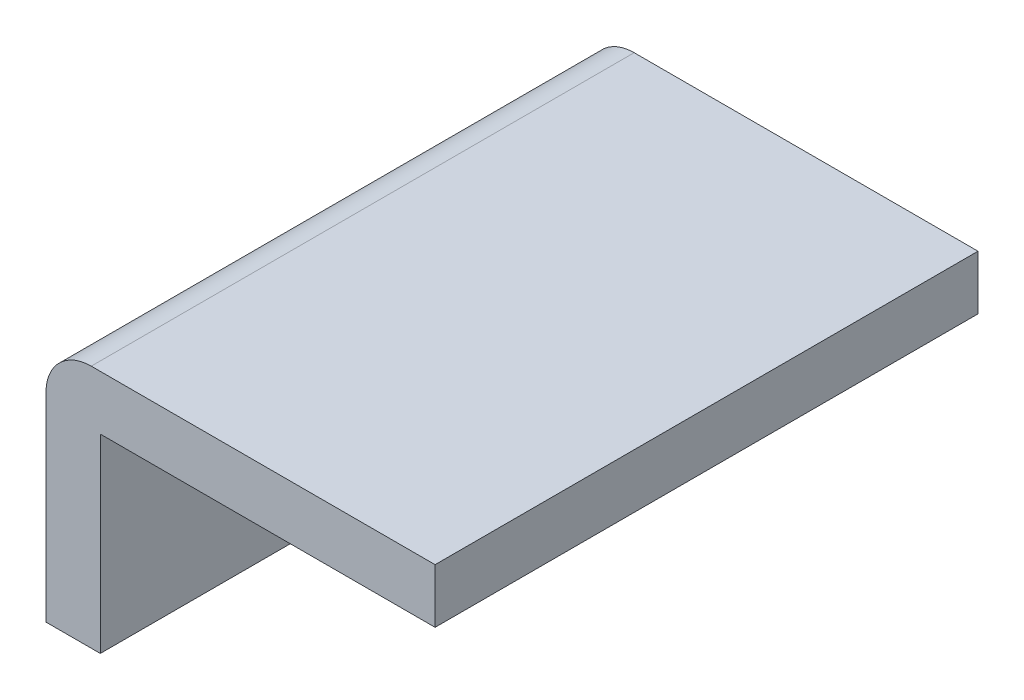
SolidWorks part; units mm, degrees
material "Acrilico TEC"
ref_plane "Front Plane" through (0, 0, 0) normal (0, 0, 1) x (1, 0, 0)
ref_plane "Top Plane" through (0, 0, 0) normal (0, 1, 0) x (1, 0, 0)
ref_plane "Right Plane" through (0, 0, 0) normal (1, 0, 0) x (0, 0, -1)
sketch "Sketch1" plane through (0, 0, 0) normal (0, 0, 1) x (1, 0, 0)
  line L0 (0, 0) -> (0, 11)
  line L1 (1, 12) -> (20, 12)
  line L2 (1.5, 0) -> (1.5, 10.5)
  line L3 (1.5, 10.5) -> (20, 10.5)
  line L4 (-1.5, 0) -> (-1.5, 11)
  line L5 (1, 13.5) -> (20, 13.5)
  line L6 (20, 13.5) -> (20, 10.5)
  line L7 (-1.5, 0) -> (1.5, 0)
  arc A0 (0, 11) -> (1, 12) centre (1, 11) cw
  arc A1 (1.5, 10.5) -> (1.5, 10.5) centre (1.5, 10.5) cw
  arc A2 (-1.5, 11) -> (1, 13.5) centre (1, 11) cw
  point P6 (0, 12)
  dimension "D3" = 1
  dimension "D1" = 20
  dimension "D2" = 12
  dimension "D4" = 1.5
  dimension "D5" = 1.5
extrude "Boss-Extrude1" add sketch "Sketch1" along normal blind 30 contours A0 L0 L7 L2 L3 L6 L1 | A2 L4 L7 L0 A0 L1 L6 L5
hole_wizard "Ø2.0mm Clearance Dowel Hole1" positions "Sketch2" profile "Sketch3" hole size "Ø2.0" standard "ISO"
sketch "Sketch2" plane through (-35.9294, 10.5, -58.5) normal (0, -1, 0) x (-1, 0, 0)
  point P0 (-26.9294, -76.5)
  point P1 (-26.9294, -70.5)
sketch "Sketch3" plane through (-9, 10.5, 18) normal (1, 0, 0) x (0, 0, -1)
  line L0 (0, 0) -> (0, 3)
  line L1 (0, 3) -> (1, 3)
  line L2 (1, 3) -> (1, 0)
  line L3 (1, 0) -> (0, 0)
  line L4 (0, -6.35) -> (0, 107.95) construction
  dimension "Thru Hole Dia." = 2
  dimension "Thru Hole Depth" = 3
